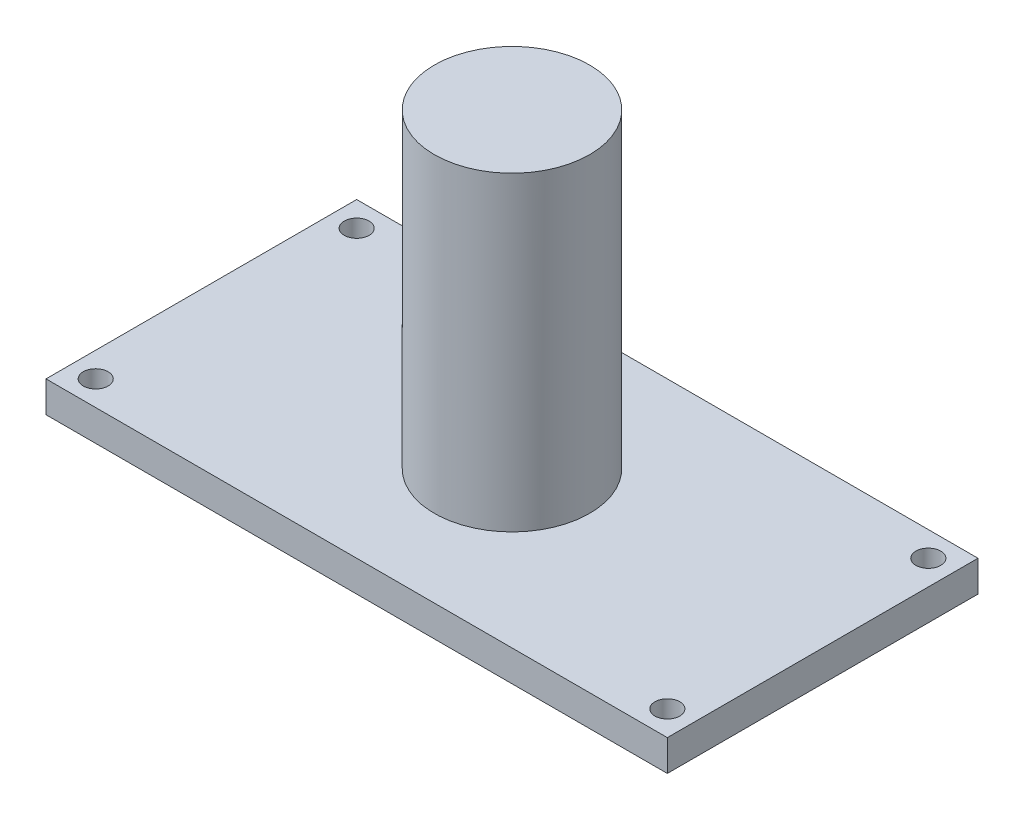
SolidWorks part; units mm, degrees
ref_plane "Front Plane" through (0, 0, 0) normal (0, 0, 1) x (1, 0, 0)
ref_plane "Top Plane" through (0, 0, 0) normal (0, 1, 0) x (1, 0, 0)
ref_plane "Right Plane" through (0, 0, 0) normal (1, 0, 0) x (0, 0, -1)
sketch "Sketch1" plane through (0, 0, 0) normal (0, 1, 0) x (1, 0, 0)
  line L1 (-100, -50) -> (100, -50)
  line L2 (-100, -50) -> (-100, 50)
  line L3 (-100, 50) -> (100, 50)
  line L4 (100, -50) -> (100, 50)
  line L5 (-100, -50) -> (100, 50) construction
  line L6 (-100, 50) -> (100, -50) construction
  circle A0 centre (-92, 42) radius 4
  circle A3 centre (-92, -42) radius 4
  circle A4 centre (92, -42) radius 4
  circle A5 centre (92, 42) radius 4
  point P0 (0, 0)
  point P8 (0, 0)
  point P9 (91.1994, 29.605)
  point P10 (0, 0)
  point P11 (0, 0)
  point P18 (0, 0)
  point P19 (0, 0)
  point P22 (-89.5487, -38.6473)
  point P23 (-91.1858, -41.8796)
  dimension "D3" = 8
  dimension "D1" = 100
  dimension "D2" = 200
  dimension "D4" = 8
  dimension "D5" = 8
  dimension "D6" = 8
  dimension "D7" = 8
  dimension "D8" = 8
  dimension "D9" = 8
  dimension "D10" = 8
  dimension "D11" = 8
extrude "Boss-Extrude1" add sketch "Sketch1" along normal blind 10
sketch "Sketch2" plane through (0, 10, 0) normal (0, 1, 0) x (1, 0, 0)
  circle A0 centre (0, 0) radius 25
  dimension "D1" = 50
extrude "Boss-Extrude2" add sketch "Sketch2" along normal blind 100
